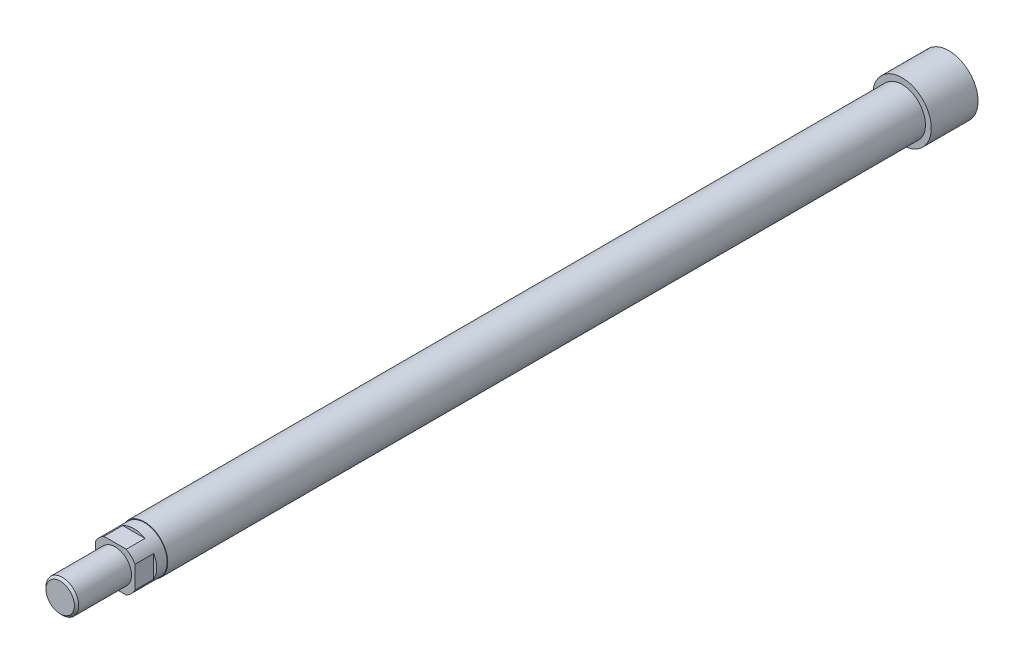
SolidWorks part; units mm, degrees
ref_plane "Front Plane" through (0, 0, 0) normal (0, 0, 1) x (1, 0, 0)
ref_plane "Top Plane" through (0, 0, 0) normal (0, 1, 0) x (1, 0, 0)
ref_plane "Right Plane" through (0, 0, 0) normal (1, 0, 0) x (0, 0, -1)
ref_plane "Plane1" through (0, 0, 0) normal (0, -1, 0) x (1, 0, 0)
sketch "Sketch1" plane through (0, 0, 0) normal (0, -1, 0) x (1, 0, 0)
  line L0 (12.5, -322) -> (0, -322)
  line L1 (0, -322) -> (0, -342)
  line L2 (0, -342) -> (12.5, -342)
  line L3 (12.5, -342) -> (12.5, -322)
  line L4 (0, -322) -> (0, -342) construction
revolve "Revolve1" add sketch "Sketch1" angle 360 about L4
sketch "Sketch2" plane through (0, 0, -322) normal (0, 0, 1) x (1, 0, 0)
  circle A0 centre (0, 0) radius 10
extrude "Boss-Extrude1" add sketch "Sketch2" along normal blind 324
sketch "Sketch3" plane through (0, 0, 2) normal (0, 0, 1) x (1, 0, 0)
  circle A0 centre (0, 0) radius 9.75
extrude "Boss-Extrude2" add sketch "Sketch3" along normal blind 12.5
sketch "Sketch4" plane through (0, 0, 14.5) normal (0, 0, 1) x (1, 0, 0)
  line L0 (-8.5, -4.7762) -> (-8.5, 4.7762)
  arc A0 (-8.5, 4.7762) -> (-8.5, -4.7762) centre (0, 0) ccw
extrude "Cut-Extrude1" cut sketch "Sketch4" against normal blind 8
sketch "Sketch5" plane through (0, 0, 14.5) normal (0, 0, 1) x (1, 0, 0)
  line L0 (4.7762, -8.5) -> (-4.7762, -8.5)
  arc A0 (-4.7762, -8.5) -> (4.7762, -8.5) centre (0, 0) ccw
extrude "Cut-Extrude2" cut sketch "Sketch5" against normal blind 8
sketch "Sketch6" plane through (0, 0, 14.5) normal (0, 0, 1) x (1, 0, 0)
  line L0 (8.5, 4.7762) -> (8.5, -4.7762)
  arc A0 (8.5, -4.7762) -> (8.5, 4.7762) centre (0, 0) ccw
extrude "Cut-Extrude3" cut sketch "Sketch6" against normal blind 8
sketch "Sketch7" plane through (0, 0, 14.5) normal (0, 0, 1) x (1, 0, 0)
  line L0 (-4.7762, 8.5) -> (4.7762, 8.5)
  arc A0 (4.7762, 8.5) -> (-4.7762, 8.5) centre (0, 0) ccw
extrude "Cut-Extrude4" cut sketch "Sketch7" against normal blind 8
sketch "Sketch8" plane through (0, 0, 14.5) normal (0, 0, 1) x (1, 0, 0)
  circle A0 centre (0, 0) radius 7
extrude "Boss-Extrude3" add sketch "Sketch8" along normal blind 23.5
chamfer "Chamfer1" distance 0.92 angle 45 1 edges at (7, 0, 38)
